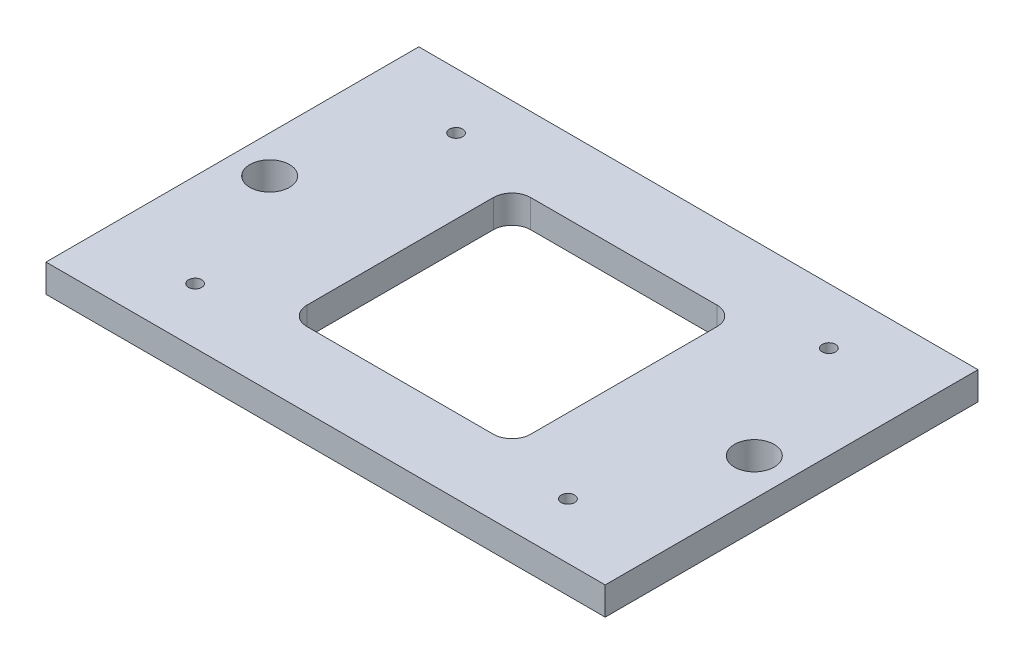
SolidWorks part; units mm, degrees
ref_plane "Front Plane" through (0, 0, 0) normal (0, 0, 1) x (1, 0, 0)
ref_plane "Top Plane" through (0, 0, 0) normal (0, 1, 0) x (1, 0, 0)
ref_plane "Right Plane" through (0, 0, 0) normal (1, 0, 0) x (0, 0, -1)
sketch "Sketch1" plane through (0, 0, 0) normal (0, 1, 0) x (1, 0, 0)
  line L1 (-47.625, 31.75) -> (47.625, 31.75)
  line L2 (-47.625, 31.75) -> (-47.625, -31.75)
  line L3 (-47.625, -31.75) -> (47.625, -31.75)
  line L4 (47.625, 31.75) -> (47.625, -31.75)
  line L5 (-47.625, 31.75) -> (47.625, -31.75) construction
  line L6 (-47.625, -31.75) -> (47.625, 31.75) construction
  point P0 (0, 0)
  dimension "D1" = 95.25
  dimension "D2" = 63.5
extrude "Boss-Extrude1" add sketch "Sketch1" along normal mid plane 4.7625
sketch "Sketch2" plane through (0, 2.3813, 0) normal (0, 1, 0) x (1, 0, 0)
  line L1 (-19.05, 19.05) -> (19.05, 19.05)
  line L2 (-19.05, 19.05) -> (-19.05, -19.05)
  line L3 (-19.05, -19.05) -> (19.05, -19.05)
  line L4 (19.05, 19.05) -> (19.05, -19.05)
  line L5 (-19.05, 19.05) -> (19.05, -19.05) construction
  line L6 (-19.05, -19.05) -> (19.05, 19.05) construction
  point P0 (0, 0)
  dimension "D1" = 38.1
  dimension "D2" = 38.1
extrude "Cut-Extrude1" cut sketch "Sketch2" against normal up to next
hole_wizard "#4-40 Tapped Hole1" positions "Sketch4" profile "Sketch3" tap size "#4-40" standard "ANSI Inch" end condition up to next
sketch "Sketch4" plane through (0, 2.3813, 0) normal (0, 1, 0) x (1, 0, 0)
  point P0 (-31.75, 22.225)
  point P2 (31.75, 22.225)
  dimension "D1" = 31.75
  dimension "D2" = 31.75
  dimension "D3" = 22.225
sketch "Sketch3" plane through (-31.75, 2.3813, -22.225) normal (1, 0, 0) x (0, 0, 1)
  line L0 (0, 0) -> (0, 4.7635)
  line L1 (0, 4.7635) -> (1.1303, 4.7635)
  line L2 (1.1303, 4.7635) -> (1.1303, 0)
  line L5 (1.1303, 0) -> (0, 0)
  line L11 (0, -6.35) -> (0, 107.95) construction
  dimension "Thru Tap Drill Dia." = 2.2606
  dimension "Thru Tap Drill Depth" = 4.7635
cosmetic thread "Hole Thread1" parameters "D2"=2.8448
cosmetic thread "Hole Thread2" parameters "D2"=2.8448
mirror "Mirror1" about plane through (0, 0, 0) normal (0, 0, 1) of "#4-40 Tapped Hole1"
hole_wizard "17/64 (0.26563) Diameter Hole1" positions "Sketch8" profile "Sketch7" hole size "17/64" standard "ANSI Inch" end condition up to next
sketch "Sketch8" plane through (0, 2.3813, 0) normal (0, 1, 0) x (1, 0, 0)
  point P0 (-41.275, 0)
  point P2 (41.275, 0)
  dimension "D1" = 41.275
  dimension "D2" = 41.275
sketch "Sketch7" plane through (-41.275, 2.3813, 0) normal (1, 0, 0) x (0, 0, 1)
  line L0 (0, 0) -> (0, 4.7625)
  line L1 (0, 4.7625) -> (3.3735, 4.7625)
  line L2 (3.3735, 4.7625) -> (3.3735, 0)
  line L5 (3.3735, 0) -> (0, 0)
  line L11 (0, -6.35) -> (0, 107.95) construction
  dimension "Thru Hole Dia." = 6.747
  dimension "Thru Hole Depth" = 4.7625
fillet "Fillet1" radius 3.175 1 edges at (-19.05, 0, -19.05)
fillet "Fillet2" radius 3.175 1 edges at (-19.05, 0, 19.05)
fillet "Fillet3" radius 3.175 1 edges at (19.05, 0, -19.05)
fillet "Fillet4" radius 3.175 1 edges at (19.05, 0, 19.05)
